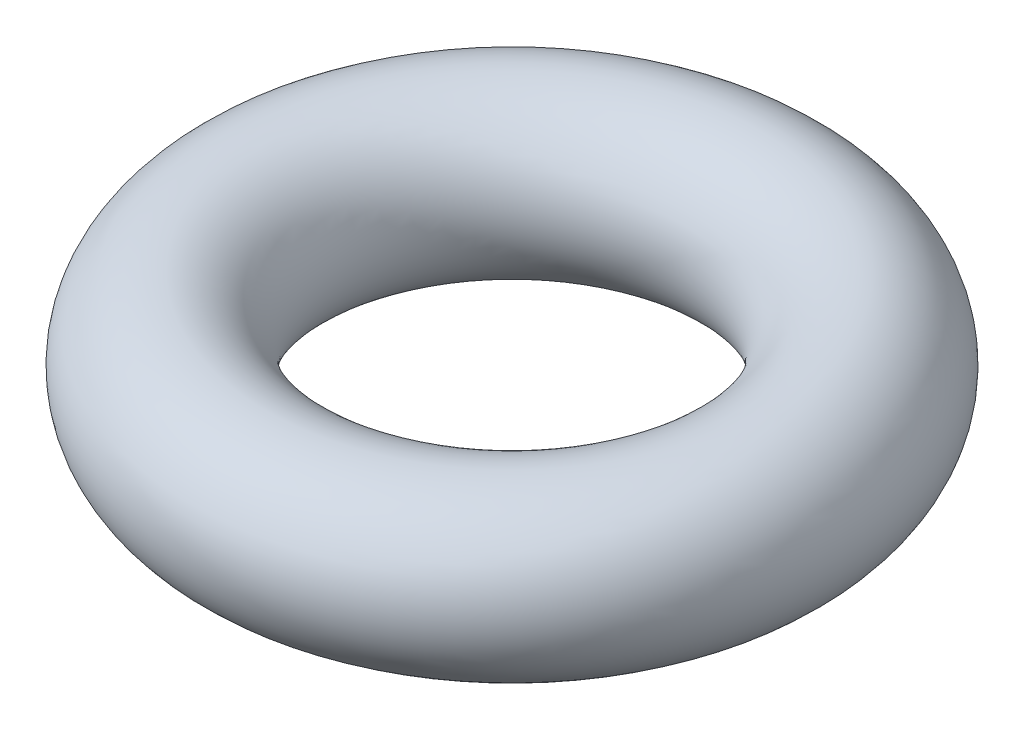
SolidWorks part; units mm, degrees
ref_plane "Front" through (0, 0, 0) normal (0, 0, 1) x (1, 0, 0)
ref_plane "Top" through (0, 0, 0) normal (0, 1, 0) x (1, 0, 0)
ref_plane "Right" through (0, 0, 0) normal (1, 0, 0) x (0, 0, -1)
sketch "Sketch1" plane through (0, 0, 0) normal (0, 0, 1) x (1, 0, 0)
  line L0 (0, -44.218) -> (0, 2166.6824) construction
  circle A0 centre (2.3876, 0) radius 0.7938
  dimension "D1" = 1.5875
  dimension "D2" = 2.3876
revolve "Revolve1" add sketch "Sketch1" angle 360 about L0
sketch "Sketch3" plane through (0, 0, 0) normal (1, 0, 0) x (0, 0, -1)
  circle A0 centre (-2.3876, 0) radius 0.7938
  circle A1 centre (2.3876, 0) radius 0.7938
  circle A2 centre (2.3876, 0) radius 0.7938
  circle A3 centre (-2.3876, 0) radius 0.7938
  point P6 (-2.3876, 0.7937)
  point P7 (2.3876, 0.7937)
  point P8 (-2.3876, -0.7938)
  point P9 (2.3876, -0.7938)
